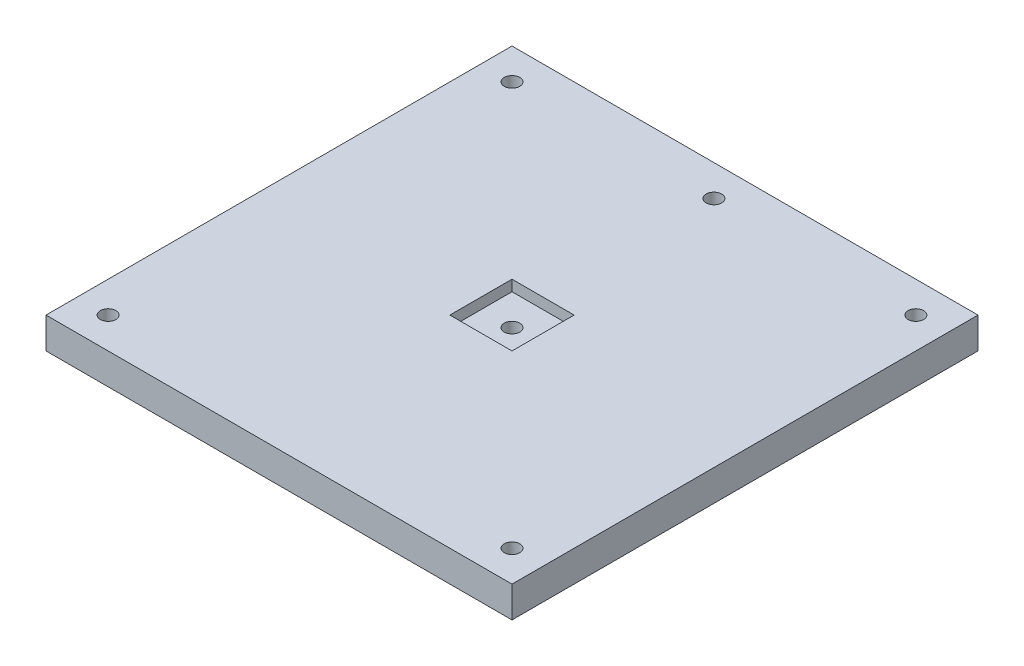
SolidWorks part; units mm, degrees
ref_plane "Plano frontal" through (0, 0, 0) normal (0, 0, 1) x (1, 0, 0)
ref_plane "Plano superior" through (0, 0, 0) normal (0, 1, 0) x (1, 0, 0)
ref_plane "Plano direito" through (0, 0, 0) normal (1, 0, 0) x (0, 0, -1)
sketch "Esboço1" plane through (0, 0, 0) normal (0, 1, 0) x (1, 0, 0)
  line L0 (124.5946, 13.6486) -> (124.5946, -286.3514) construction
  line L1 (-25.4054, -286.3514) -> (274.5946, -286.3514)
  line L2 (-25.4054, -286.3514) -> (-25.4054, 13.6486)
  line L3 (-25.4054, 13.6486) -> (274.5946, 13.6486)
  line L4 (274.5946, -286.3514) -> (274.5946, 13.6486)
  line L5 (-25.4054, -136.3514) -> (274.5946, -136.3514) construction
  circle A0 centre (-5.4054, -6.3514) radius 5
  circle A1 centre (254.5946, -6.3514) radius 5
  circle A2 centre (254.5946, -266.3514) radius 5
  circle A3 centre (-5.4054, -266.3514) radius 5
  circle A4 centre (124.5946, -6.3514) radius 5
  dimension "D3" = 10
  dimension "D4" = 20
  dimension "D5" = 20
  dimension "D6" = 20
  dimension "D1" = 300
  dimension "D2" = 300
extrude "Ressalto-extrusão1" add sketch "Esboço1" along normal blind 20
sketch "Esboço2" plane through (0, 20, 0) normal (0, 1, 0) x (1, 0, 0)
  line L0 (-25.4054, -136.3514) -> (274.5946, -136.3514) construction
  line L1 (-25.4054, 13.6486) -> (-25.4054, -286.3514) construction
  line L2 (274.5946, -286.3514) -> (274.5946, 13.6486) construction
  line L3 (274.5946, 13.6486) -> (-25.4054, 13.6486) construction
  line L4 (124.5946, 13.6486) -> (124.5946, -286.3514) construction
  line L5 (-25.4054, -286.3514) -> (274.5946, -286.3514) construction
  line L7 (104.5946, -156.3514) -> (144.5946, -156.3514)
  line L8 (104.5946, -156.3514) -> (104.5946, -116.3514)
  line L9 (104.5946, -116.3514) -> (144.5946, -116.3514)
  line L10 (144.5946, -156.3514) -> (144.5946, -116.3514)
  line L11 (104.5946, -156.3514) -> (144.5946, -116.3514) construction
  line L12 (104.5946, -116.3514) -> (144.5946, -156.3514) construction
  point P12 (124.5946, -136.3514)
  dimension "D1" = 40
  dimension "D2" = 40
extrude "Corte-extrusão1" cut sketch "Esboço2" against normal blind 7
sketch "Esboço3" plane through (0, 13, 0) normal (0, 1, 0) x (1, 0, 0)
  line L0 (104.5946, -136.3514) -> (144.5946, -136.3514) construction
  line L1 (104.5946, -116.3514) -> (104.5946, -156.3514) construction
  line L2 (144.5946, -156.3514) -> (144.5946, -116.3514) construction
  line L3 (124.5946, -116.3514) -> (124.5946, -156.3514) construction
  line L4 (144.5946, -116.3514) -> (104.5946, -116.3514) construction
  line L5 (104.5946, -156.3514) -> (144.5946, -156.3514) construction
  circle A0 centre (124.5946, -136.3514) radius 5
  dimension "D1" = 10
extrude "Corte-extrusão2" cut sketch "Esboço3" against normal through all contours A0
